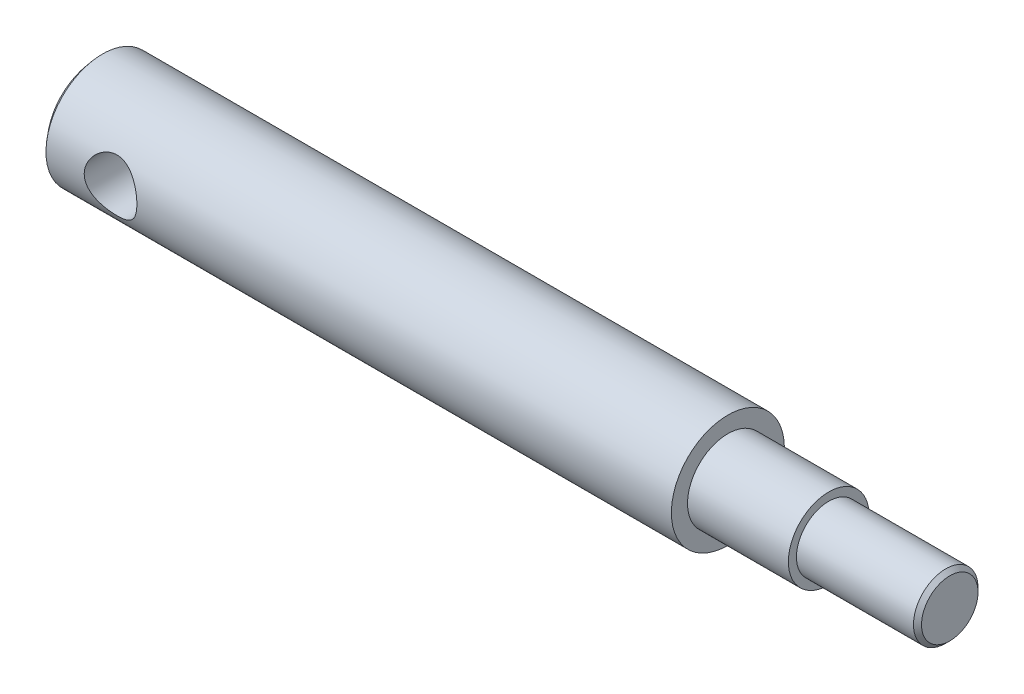
SolidWorks part; units mm, degrees
ref_plane "Front Plane" through (0, 0, 0) normal (0, 0, 1) x (1, 0, 0)
ref_plane "Top Plane" through (0, 0, 0) normal (0, 1, 0) x (1, 0, 0)
ref_plane "Right Plane" through (0, 0, 0) normal (1, 0, 0) x (0, 0, -1)
sketch "Sketch1" plane through (0, 0, 0) normal (0, 0, 1) x (1, 0, 0)
  line L0 (0, 0) -> (216, 0)
  line L1 (216, 0) -> (216, 7)
  line L2 (215, 8) -> (186, 8)
  line L3 (186, 8) -> (186, 10)
  line L4 (186, 10) -> (161, 10)
  line L5 (161, 10) -> (161, 14)
  line L6 (161, 14) -> (6, 14)
  line L7 (216, 7) -> (215, 8)
  arc A0 (6, 14) -> (0, 0) centre (21.9709, -1.1304) ccw
  point P4 (216, 8)
  dimension "D8" = 22
  dimension "D1" = 155
  dimension "D2" = 25
  dimension "D3" = 30
  dimension "D4" = 8
  dimension "D5" = 6
  dimension "D6" = 10
  dimension "D7" = 14
revolve "Revolve2" add sketch "Sketch1" angle 360 about L0
cosmetic thread "Cosmetic Thread2" parameters "D2"=13.797
sketch "Sketch3" plane through (0, 0, 0) normal (0, 0, 1) x (1, 0, 0)
  circle A0 centre (22, 0) radius 6.525
  dimension "D1" = 13.05
  dimension "D2" = 22
extrude "Cut-Extrude4" cut sketch "Sketch3" against normal mid plane 109
